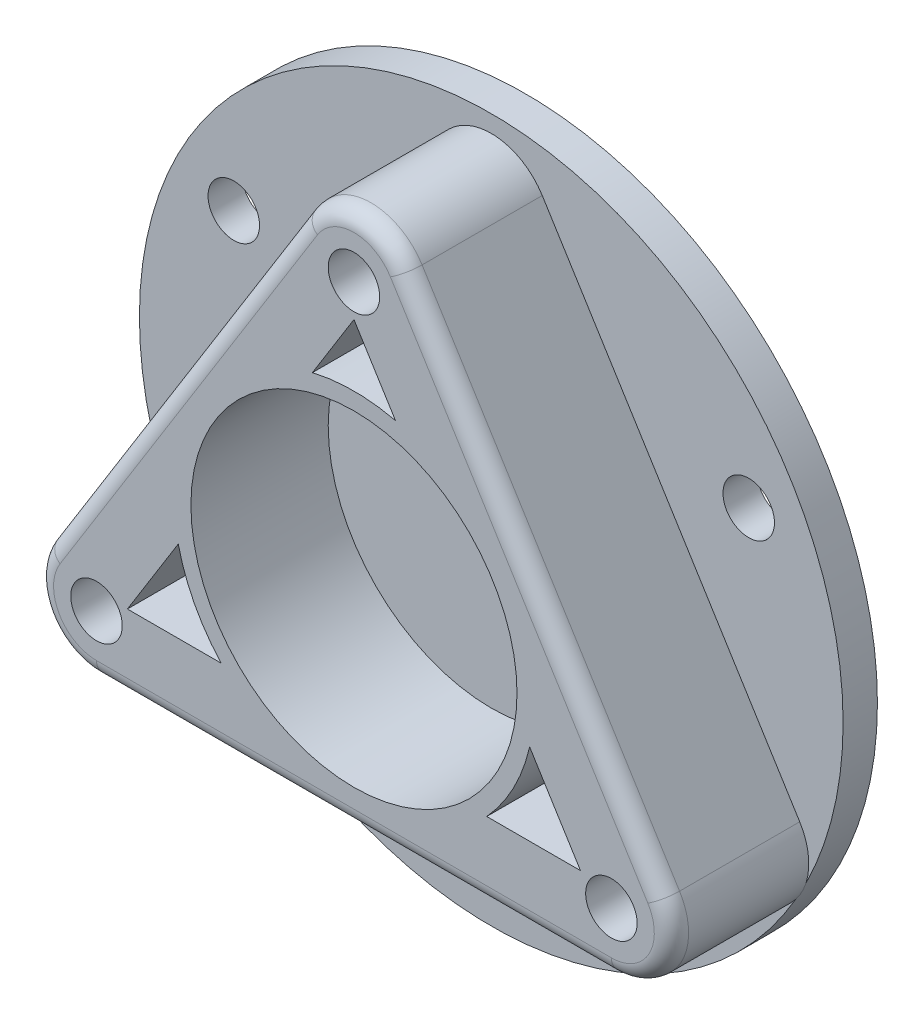
SolidWorks part; units mm, degrees
ref_plane "Alzado" through (0, 0, 0) normal (0, 0, 1) x (1, 0, 0)
ref_plane "Planta" through (0, 0, 0) normal (0, 1, 0) x (1, 0, 0)
ref_plane "Vista lateral" through (0, 0, 0) normal (1, 0, 0) x (0, 0, -1)
sketch "Croquis1" plane through (0, 0, 0) normal (0, 0, 1) x (1, 0, 0)
  line L0 (0, 0) -> (0, -16) construction
  circle A1 centre (0, 0) radius 20.5
  circle A2 centre (15, 8.1) radius 1.5
  circle A3 centre (0, -16) radius 1.5
  circle A4 centre (-15, 8.1) radius 1.5
  dimension "D1" = 8.1
  dimension "D2" = 41
  dimension "D3" = 3
  dimension "D4" = 3
  dimension "D5" = 15
  dimension "D6" = 16
extrude "Saliente-Extruir1" add sketch "Croquis1" along normal blind 2
sketch "Croquis2" plane through (0, 0, 2) normal (0, 0, 1) x (1, 0, 0)
  circle A0 centre (0, 0) radius 9.5
  circle A1 centre (0, 0) radius 11.5
  dimension "D1" = 19
  dimension "D2" = 2
extrude "Saliente-Extruir2" add sketch "Croquis2" along normal blind 8
sketch "Croquis3" plane through (0, 0, 2) normal (0, 0, 1) x (1, 0, 0)
  line L0 (0, 0) -> (20.5, 0) construction
  line L1 (-15, -11.6) -> (15, -11.6)
  line L2 (17.9715, -6.2505) -> (2.9715, 17.8495)
  line L3 (-2.9715, 17.8495) -> (-17.9715, -6.2505)
  circle A0 centre (0, 0) radius 20.5 construction
  circle A1 centre (-15, 8.1) radius 1.5 construction
  circle A2 centre (15, 8.1) radius 1.5 construction
  circle A3 centre (0, -16) radius 1.5 construction
  circle A4 centre (-15, 8.1) radius 1.5 construction
  circle A5 centre (15, 8.1) radius 1.5 construction
  circle A6 centre (0, -16) radius 1.5 construction
  circle A7 centre (15, -8.1) radius 1.5
  circle A8 centre (-15, -8.1) radius 1.5
  circle A9 centre (0, 16) radius 1.5
  arc A10 (2.9715, 17.8495) -> (-2.9715, 17.8495) centre (0, 16) ccw
  arc A11 (15, -11.6) -> (17.9715, -6.2505) centre (15, -8.1) ccw
  arc A12 (-17.9715, -6.2505) -> (-15, -11.6) centre (-15, -8.1) ccw
  circle A16 centre (0, 0) radius 9.5 construction
  circle A18 centre (0, 0) radius 9.5
  point P30 (0, 0)
  point P31 (15, -11.6)
  point P32 (15, -11.6)
  point P33 (15, -11.6)
  dimension "D1" = 7
  dimension "D2" = 7
  dimension "D3" = 7
extrude "Saliente-Extruir4" add sketch "Croquis3" along normal up to surface (8 mm away) up to face at (11.5, 0, 10)
fillet "Redondeo1" radius 1 6 edges at (0, 19.5, 10) (10.4715, 5.7995, 10) (18.0597, -9.7995, 10) (0, -11.6, 10) (-18.0597, -9.7995, 10) (-10.4715, 5.7995, 10)
sketch "Croquis4" plane through (0, 0, 10) normal (0, 0, 1) x (1, 0, 0)
  line L12 (-10.2362, -2.3387) -> (-13.1997, -7.1)
  line L13 (2.4215, 10.217) -> (0, 14.1075)
  line L14 (7.7356, -7.1) -> (13.1997, -7.1)
  line L15 (13.1997, -7.1) -> (0, 14.1075)
  line L16 (0, 14.1075) -> (-13.1997, -7.1)
  line L17 (-13.1997, -7.1) -> (13.1997, -7.1)
  line L18 (13.1997, -7.1) -> (10.2362, -2.3387)
  line L19 (0, 14.1075) -> (-2.4215, 10.217)
  line L20 (-13.1997, -7.1) -> (-7.7356, -7.1)
  circle A9 centre (0, 0) radius 10.5
  arc A10 (-10.2362, -2.3387) -> (-7.7356, -7.1) centre (0, 0) ccw
  arc A13 (2.4215, 10.217) -> (-2.4215, 10.217) centre (0, 0) ccw
  arc A14 (7.7356, -7.1) -> (10.2362, -2.3387) centre (0, 0) ccw
  dimension "D1" = 1
  dimension "D2" = 3.5
extrude "Cortar-Extruir1" cut sketch "Croquis4" against normal up to surface (8 mm away) up to face at (1.5, -16, 2)
